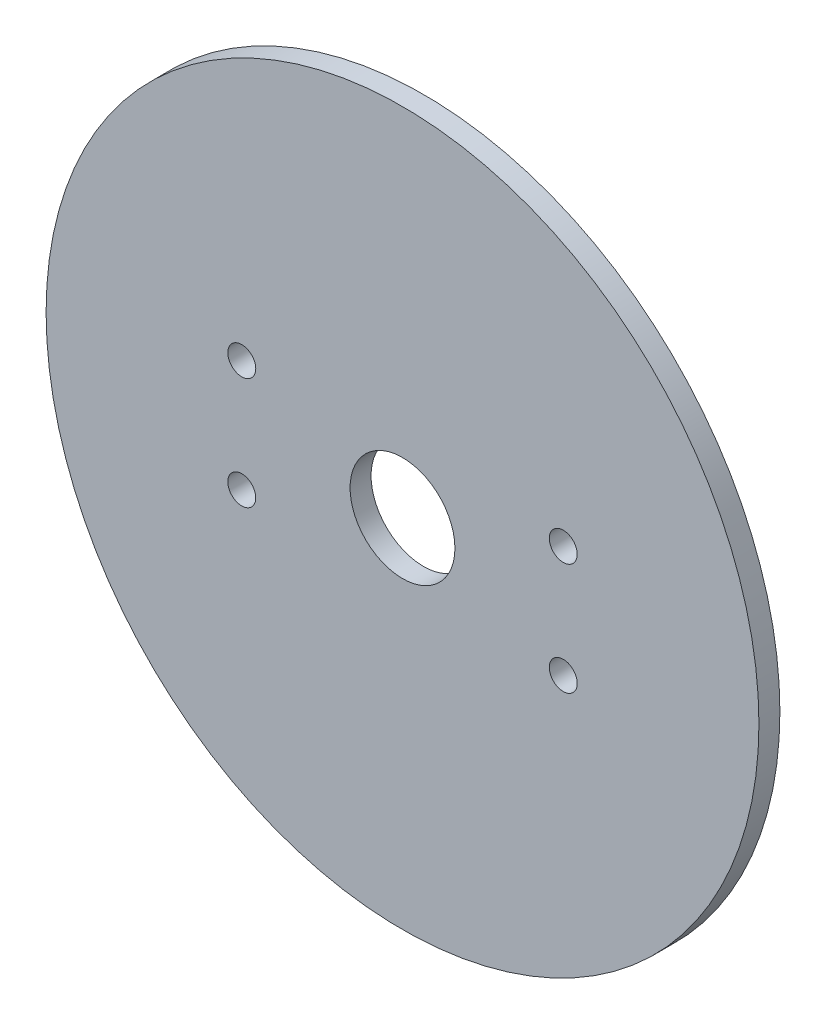
SolidWorks part; units mm, degrees
material "아크릴(내충격성)"
ref_plane "정면" through (0, 0, 0) normal (0, 0, 1) x (1, 0, 0)
ref_plane "윗면" through (0, 0, 0) normal (0, 1, 0) x (1, 0, 0)
ref_plane "우측면" through (0, 0, 0) normal (1, 0, 0) x (0, 0, -1)
sketch "스케치1" plane through (0, 0, 0) normal (0, 0, 1) x (1, 0, 0)
  circle A0 centre (0, 0) radius 51
  dimension "D1" = 102
extrude "보스-돌출1" add sketch "스케치1" along normal blind 3
sketch "스케치2" plane through (0, 0, 3) normal (0, 0, 1) x (1, 0, 0)
  circle A0 centre (0, 0) radius 7.5
  dimension "D1" = 15
extrude "컷-돌출1" cut sketch "스케치2" against normal blind 3
sketch "스케치3" plane through (0, 0, 3) normal (0, 0, 1) x (1, 0, 0)
  line L0 (-56.0789, 0) -> (55.5902, 0) construction
  line L1 (0, 49.5425) -> (0, -49.6646) construction
  line L2 (-56.0789, -15) -> (55.5902, -15)
  line L3 (-56.0789, 15) -> (55.5902, 15)
  line L4 (-30, 49.5425) -> (-30, -49.6646)
  line L5 (30, 49.5425) -> (30, -49.6646)
  circle A0 centre (-23, 8) radius 2
  circle A1 centre (-23, -8) radius 2
  circle A2 centre (23, -8) radius 2
  circle A3 centre (23, 8) radius 2
  dimension "D5" = 4
  dimension "D6" = 7
  dimension "D7" = 7
  dimension "D1" = 15
  dimension "D2" = 15
  dimension "D3" = 30
  dimension "D4" = 30
extrude "컷-돌출2" cut sketch "스케치3" against normal blind 3 contours A0 | A1 | A2 | A3
